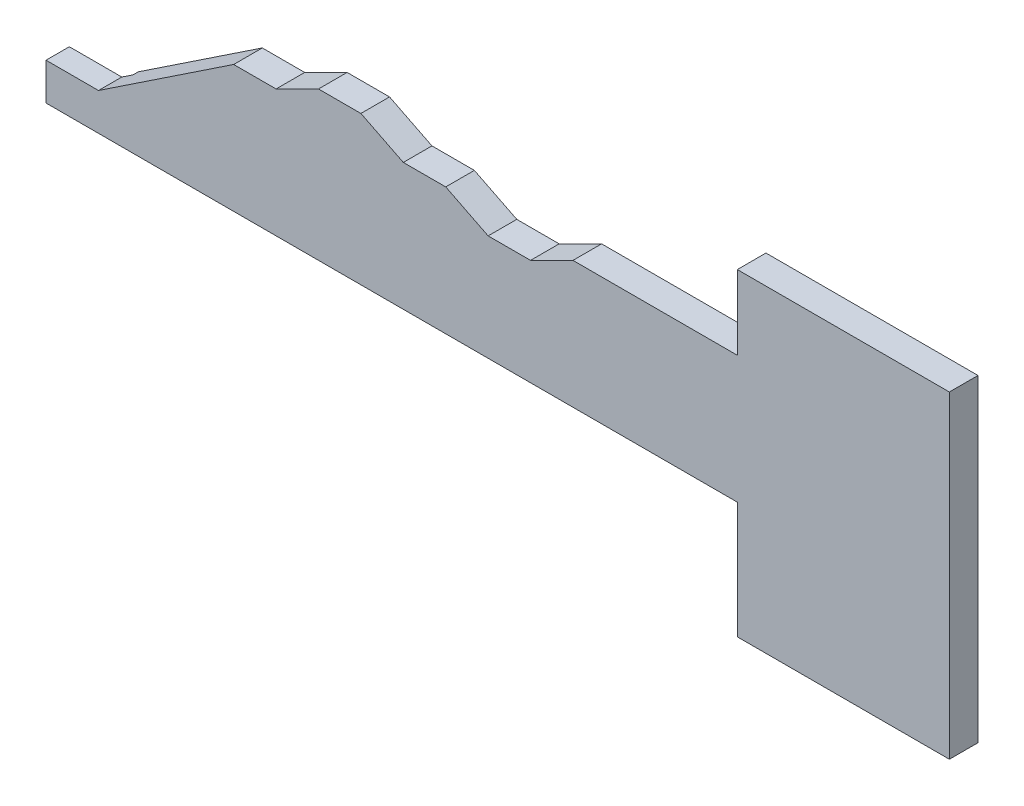
SolidWorks part; units mm, degrees
ref_plane "Front Plane" through (0, 0, 0) normal (0, 0, 1) x (1, 0, 0)
ref_plane "Top Plane" through (0, 0, 0) normal (0, 1, 0) x (1, 0, 0)
ref_plane "Right Plane" through (0, 0, 0) normal (1, 0, 0) x (0, 0, -1)
sketch "Sketch1" plane through (0, 0, 0) normal (0, 0, 1) x (1, 0, 0)
  line L0 (0, 15) -> (0, -15)
  line L1 (0, -15) -> (20, -15)
  line L2 (20, -15) -> (20, 15)
  line L3 (20, 15) -> (0, 15)
  line L4 (0, 0) -> (-60.5, 0) construction
  line L5 (0, -4) -> (-60.5, -4)
  line L6 (-60.5, -4) -> (-60.5, 0)
  line L7 (0, 8) -> (-15.5, 8)
  line L8 (-15.5, 8) -> (-19.5, 6)
  line L9 (-19.5, 6) -> (-23.5, 6)
  line L10 (-23.5, 6) -> (-27.5, 8)
  line L11 (-27.5, 8) -> (-31.5, 8)
  line L12 (-31.5, 8) -> (-35.5, 10)
  line L13 (-35.5, 10) -> (-39.5, 10)
  line L14 (-39.5, 10) -> (-43.5, 8)
  line L15 (-43.5, 8) -> (-47.5, 8)
  line L16 (-60.25, -0.5) -> (-47.5, 8)
  line L17 (-60.5, -1.15) -> (0, -1.15) construction
  line L18 (-39.5, 10) -> (-39.5, 0) construction
  line L19 (-31.5, 8) -> (-31.5, 0) construction
  line L20 (-23.5, 6) -> (-23.5, 0) construction
  line L21 (-15.5, 8) -> (-15.5, 0) construction
  line L22 (-47.5, 8) -> (-47.5, 0) construction
  line L23 (-60.25, -0.5) -> (-59.5, 0)
  line L24 (-60.5, -4) -> (-65.2, -4)
  line L25 (-60.5, -4) -> (-60.5, -0.5)
  line L26 (-60.5, -0.5) -> (-65.2, -0.5)
  line L27 (-65.2, -4) -> (-65.2, -0.5)
  line L28 (-60.25, -0.5) -> (-60.5, -0.5)
  point P4 (0, 0)
  point P23 (-60, -0.5)
  dimension "D1" = 4
  dimension "D2" = 2.85
  dimension "D3" = 8
  dimension "D4" = 8
  dimension "D5" = 6
  dimension "D6" = 8
  dimension "D7" = 10
  dimension "D8" = 8
  dimension "D9" = 4
  dimension "D10" = 8
  dimension "D11" = 8
  dimension "D12" = 8
  dimension "D13" = 60.5
  dimension "D14" = 1
  dimension "D15" = 15.5
  dimension "D16" = 3.5
  dimension "D17" = 4.7
  dimension "D18" = 20
  dimension "D19" = 30
extrude "Boss-Extrude1" add sketch "Sketch1" along normal blind 2.7 contours L16 L6 L5 L0 L7 L8 L9 L10 L11 L12 L13 L14 L15 | L2 L3 L0 L1 | L27 L24 L6 L26 | L26 L6 L16
sketch "Sketch2" plane through (0, 0, 2.7) normal (0, 0, 1) x (1, 0, 0)
  line L0 (20, -1.2) -> (-65.2, -1.2)
  line L1 (20, -15) -> (20, 15) construction
  line L2 (0, -4) -> (-65.2, -4) construction
  line L3 (20, 0.2) -> (-65.2, 0.2)
  line L4 (-65.2, -1.2) -> (-65.2, 0.2)
  line L5 (3, 0.2) -> (3, -1.2)
  line L8 (0, -4) -> (0, -15) construction
  line L9 (-65.2, -4) -> (-65.2, -0.5) construction
  dimension "D1" = 2.8
  dimension "D2" = 1.4
  dimension "D3" = 3
extrude "Cut-Extrude1" cut sketch "Sketch2" along normal blind 0.5 from surface at -2.7
